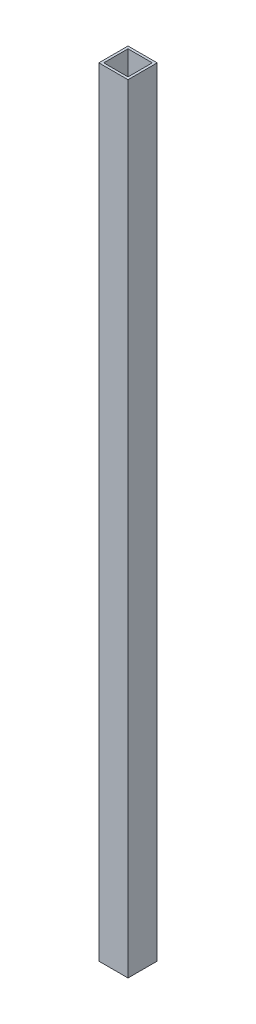
SolidWorks part; units mm, degrees
ref_plane "Front Plane" through (0, 0, 0) normal (0, 0, 1) x (1, 0, 0)
ref_plane "Top Plane" through (0, 0, 0) normal (0, 1, 0) x (1, 0, 0)
ref_plane "Right Plane" through (0, 0, 0) normal (1, 0, 0) x (0, 0, -1)
sketch "Sketch1" plane through (0, 0, 0) normal (0, 1, 0) x (1, 0, 0)
  line L1 (0, 0) -> (19.05, 0)
  line L2 (0, 0) -> (0, 19.05)
  line L3 (0, 19.05) -> (19.05, 19.05)
  line L4 (19.05, 0) -> (19.05, 19.05)
  dimension "D1" = 19.05
  dimension "D2" = 19.05
extrude "Extrude-Thin1" add sketch "Sketch1" along normal blind 508 thin thin type one direction reverse wall 1.5875
